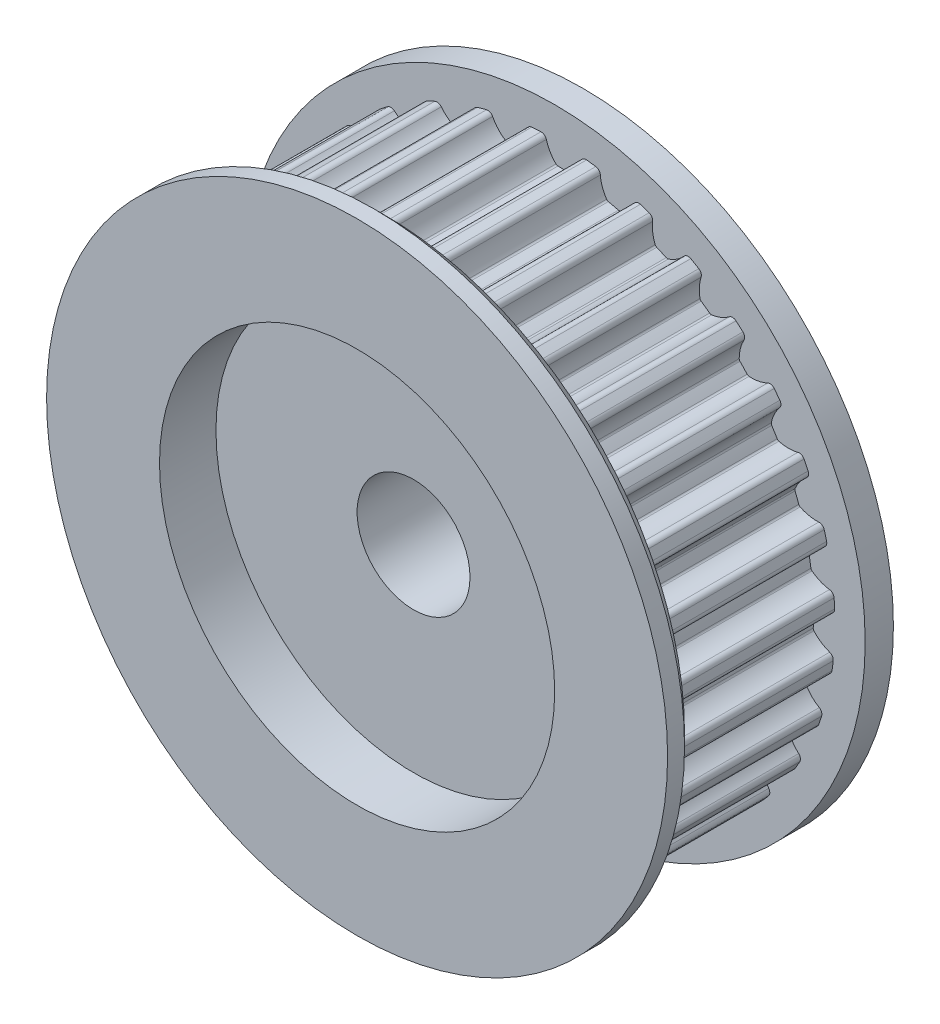
SolidWorks part; units mm, degrees
ref_plane "Front Plane" through (0, 0, 0) normal (0, 0, 1) x (1, 0, 0)
ref_plane "Top Plane" through (0, 0, 0) normal (0, 1, 0) x (1, 0, 0)
ref_plane "Right Plane" through (0, 0, 0) normal (1, 0, 0) x (0, 0, -1)
sketch "Model" plane through (0, 0, 0) normal (0, 0, 1) x (1, 0, 0)
  arc B0 (-2.731, 9.5491) -> (-2.8685, 9.3561) centre (-2.6788, 9.3665) ccw
  arc B1 (-3.0037, 8.6965) -> (-2.8685, 9.3561) centre (-4.1915, 9.2836) ccw
  arc B2 (-3.06, 8.6465) -> (-3.0037, 8.6965) centre (-3.0934, 8.7408) ccw
  arc B3 (-3.06, 8.6465) -> (-3.4049, 8.5166) centre (0, 0) ccw
  arc B4 (-3.4802, 8.517) -> (-3.4049, 8.5166) centre (-3.442, 8.6094) ccw
  arc B5 (-4.017, 8.9235) -> (-3.4802, 8.517) centre (-2.9749, 9.7419) ccw
  arc B6 (-4.017, 8.9235) -> (-4.2477, 8.9779) centre (-4.1664, 8.8061) ccw
  arc B7 (-4.2477, 8.9779) -> (-4.5415, 8.8329) centre (0, 0) ccw
  arc B8 (-4.5415, 8.8329) -> (-4.6387, 8.6167) centre (-4.4546, 8.6639) ccw
  arc B9 (-4.6426, 7.9434) -> (-4.6387, 8.6167) centre (-5.9221, 8.2875) ccw
  arc B10 (-4.688, 7.8834) -> (-4.6426, 7.9434) centre (-4.7392, 7.9693) ccw
  arc B11 (-4.688, 7.8834) -> (-5.001, 7.6887) centre (0, 0) ccw
  arc B12 (-5.0749, 7.6744) -> (-5.001, 7.6887) centre (-5.0555, 7.7725) ccw
  arc B13 (-5.6807, 7.9683) -> (-5.0749, 7.6744) centre (-4.8183, 8.9743) ccw
  arc B14 (-5.6807, 7.9683) -> (-5.9175, 7.9767) centre (-5.8043, 7.8241) ccw
  arc B15 (-5.9175, 7.9767) -> (-6.1774, 7.7771) centre (0, 0) ccw
  arc B16 (-6.1774, 7.7771) -> (-6.2306, 7.5462) centre (-6.0593, 7.6284) ccw
  arc B17 (-6.1031, 6.885) -> (-6.2306, 7.5462) centre (-7.4251, 6.9729) ccw
  arc B18 (-6.1359, 6.8173) -> (-6.1031, 6.885) centre (-6.2028, 6.8916) ccw
  arc B19 (-6.1359, 6.8173) -> (-6.4049, 6.5653) centre (0, 0) ccw
  arc B20 (-6.4746, 6.5369) -> (-6.4049, 6.5653) centre (-6.4747, 6.6369) ccw
  arc B21 (-7.1261, 6.707) -> (-6.4746, 6.5369) centre (-6.4766, 7.8619) ccw
  arc B22 (-7.1261, 6.707) -> (-7.36, 6.669) centre (-7.2192, 6.5414) ccw
  arc B23 (-7.36, 6.669) -> (-7.576, 6.4226) centre (0, 0) ccw
  arc B24 (-7.576, 6.4226) -> (-7.583, 6.1857) centre (-7.431, 6.2997) ccw
  arc B25 (-7.329, 5.5621) -> (-7.583, 6.1857) centre (-8.6428, 5.3904) ccw
  arc B26 (-7.348, 5.4893) -> (-7.329, 5.5621) centre (-7.4281, 5.5491) ccw
  arc B27 (-7.348, 5.4893) -> (-7.5626, 5.1896) centre (0, 0) ccw
  arc B28 (-7.6254, 5.1481) -> (-7.5626, 5.1896) centre (-7.6451, 5.2462) ccw
  arc B29 (-8.2976, 5.1879) -> (-7.6254, 5.1481) centre (-7.8859, 6.4473) ccw
  arc B30 (-8.2976, 5.1879) -> (-8.5196, 5.1049) centre (-8.3567, 5.0073) ccw
  arc B31 (-8.5196, 5.1049) -> (-8.6834, 4.8211) centre (0, 0) ccw
  arc B32 (-8.6834, 4.8211) -> (-8.6441, 4.5874) centre (-8.5173, 4.7289) ccw
  arc B33 (-8.2733, 4.0254) -> (-8.6441, 4.5874) centre (-9.5284, 3.6007) ccw
  arc B34 (-8.2777, 3.9503) -> (-8.2733, 4.0254) centre (-8.368, 3.9933) ccw
  arc B35 (-8.2777, 3.9503) -> (-8.4298, 3.6145) centre (0, 0) ccw
  arc B36 (-8.4833, 3.5616) -> (-8.4298, 3.6145) centre (-8.5217, 3.6539) ccw
  arc B37 (-9.1503, 3.4694) -> (-8.4833, 3.5616) centre (-8.9922, 4.7849) ccw
  arc B38 (-9.1503, 3.4694) -> (-9.3519, 3.3448) centre (-9.173, 3.2808) ccw
  arc B39 (-9.3519, 3.3448) -> (-9.4571, 3.0345) centre (0, 0) ccw
  arc B40 (-9.4571, 3.0345) -> (-9.3729, 2.8129) centre (-9.2762, 2.9764) ccw
  arc B41 (-8.8996, 2.334) -> (-9.3729, 2.8129) centre (-10.0477, 1.6726) ccw
  arc B42 (-8.8893, 2.2594) -> (-8.8996, 2.334) centre (-8.9863, 2.2841) ccw
  arc B43 (-8.8893, 2.2594) -> (-8.9729, 1.9005) centre (0, 0) ccw
  arc B44 (-9.0151, 1.8381) -> (-8.9729, 1.9005) centre (-9.0708, 1.9212) ccw
  arc B45 (-9.6513, 1.6176) -> (-9.0151, 1.8381) centre (-9.7529, 2.9387) ccw
  arc B46 (-9.6513, 1.6176) -> (-9.8247, 1.456) centre (-9.6367, 1.4282) ccw
  arc B47 (-9.8247, 1.456) -> (-9.8674, 1.1312) centre (0, 0) ccw
  arc B48 (-9.8674, 1.1312) -> (-9.7416, 0.9303) centre (-9.6786, 1.1095) ccw
  arc B49 (-9.184, 0.5529) -> (-9.7416, 0.9303) centre (-10.181, -0.3198) ccw
  arc B50 (-9.1593, 0.4818) -> (-9.184, 0.5529) centre (-9.2592, 0.4871) ccw
  arc B51 (-9.1593, 0.4818) -> (-9.1713, 0.1134) centre (0, 0) ccw
  arc B52 (-9.2005, 0.044) -> (-9.1713, 0.1134) centre (-9.2713, 0.1147) ccw
  arc B53 (-9.7814, -0.2963) -> (-9.2005, 0.044) centre (-10.1388, 0.9796) ccw
  arc B54 (-9.7814, -0.2963) -> (-9.92, -0.4886) centre (-9.7302, -0.4793) ccw
  arc B55 (-9.92, -0.4886) -> (-9.8985, -0.8156) centre (0, 0) ccw
  arc B56 (-9.8985, -0.8156) -> (-9.7359, -0.9881) centre (-9.7091, -0.8) ccw
  arc B57 (-9.1154, -1.2494) -> (-9.7359, -0.9881) centre (-9.923, -2.2998) ccw
  arc B58 (-9.0773, -1.3143) -> (-9.1154, -1.2494) centre (-9.1763, -1.3287) ccw
  arc B59 (-9.0773, -1.3143) -> (-9.0172, -1.678) centre (0, 0) ccw
  arc B60 (-9.0323, -1.7517) -> (-9.0172, -1.678) centre (-9.1155, -1.6963) ccw
  arc B61 (-9.5357, -2.1989) -> (-9.0323, -1.7517) centre (-10.1351, -1.0172) ccw
  arc B62 (-9.5357, -2.1989) -> (-9.634, -2.4145) centre (-9.4497, -2.3684) ccw
  arc B63 (-9.634, -2.4145) -> (-9.5491, -2.731) centre (0, 0) ccw
  arc B64 (-9.5491, -2.731) -> (-9.3561, -2.8685) centre (-9.3665, -2.6788) ccw
  arc B65 (-8.6965, -3.0037) -> (-9.3561, -2.8685) centre (-9.2836, -4.1915) ccw
  arc B66 (-8.6465, -3.06) -> (-8.6965, -3.0037) centre (-8.7408, -3.0934) ccw
  arc B67 (-8.6465, -3.06) -> (-8.5166, -3.4049) centre (0, 0) ccw
  arc B68 (-8.517, -3.4802) -> (-8.5166, -3.4049) centre (-8.6094, -3.442) ccw
  arc B69 (-8.9235, -4.017) -> (-8.517, -3.4802) centre (-9.7419, -2.9749) ccw
  arc B70 (-8.9235, -4.017) -> (-8.9779, -4.2477) centre (-8.8061, -4.1664) ccw
  arc B71 (-8.9779, -4.2477) -> (-8.8329, -4.5415) centre (0, 0) ccw
  arc B72 (-8.8329, -4.5415) -> (-8.6167, -4.6387) centre (-8.6639, -4.4546) ccw
  arc B73 (-7.9434, -4.6426) -> (-8.6167, -4.6387) centre (-8.2875, -5.9221) ccw
  arc B74 (-7.8834, -4.688) -> (-7.9434, -4.6426) centre (-7.9693, -4.7392) ccw
  arc B75 (-7.8834, -4.688) -> (-7.6887, -5.001) centre (0, 0) ccw
  arc B76 (-7.6744, -5.0749) -> (-7.6887, -5.001) centre (-7.7725, -5.0555) ccw
  arc B77 (-7.9683, -5.6807) -> (-7.6744, -5.0749) centre (-8.9743, -4.8183) ccw
  arc B78 (-7.9683, -5.6807) -> (-7.9767, -5.9175) centre (-7.8241, -5.8043) ccw
  arc B79 (-7.9767, -5.9175) -> (-7.7771, -6.1774) centre (0, 0) ccw
  arc B80 (-7.7771, -6.1774) -> (-7.5462, -6.2306) centre (-7.6284, -6.0593) ccw
  arc B81 (-6.885, -6.1031) -> (-7.5462, -6.2306) centre (-6.9729, -7.4251) ccw
  arc B82 (-6.8173, -6.1359) -> (-6.885, -6.1031) centre (-6.8916, -6.2028) ccw
  arc B83 (-6.8173, -6.1359) -> (-6.5653, -6.4049) centre (0, 0) ccw
  arc B84 (-6.5369, -6.4746) -> (-6.5653, -6.4049) centre (-6.6369, -6.4747) ccw
  arc B85 (-6.707, -7.1261) -> (-6.5369, -6.4746) centre (-7.8619, -6.4766) ccw
  arc B86 (-6.707, -7.1261) -> (-6.669, -7.36) centre (-6.5414, -7.2192) ccw
  arc B87 (-6.669, -7.36) -> (-6.4226, -7.576) centre (0, 0) ccw
  arc B88 (-6.4226, -7.576) -> (-6.1857, -7.583) centre (-6.2997, -7.431) ccw
  arc B89 (-5.5621, -7.329) -> (-6.1857, -7.583) centre (-5.3904, -8.6428) ccw
  arc B90 (-5.4893, -7.348) -> (-5.5621, -7.329) centre (-5.5491, -7.4281) ccw
  arc B91 (-5.4893, -7.348) -> (-5.1896, -7.5626) centre (0, 0) ccw
  arc B92 (-5.1481, -7.6254) -> (-5.1896, -7.5626) centre (-5.2462, -7.6451) ccw
  arc B93 (-5.1879, -8.2976) -> (-5.1481, -7.6254) centre (-6.4473, -7.8859) ccw
  arc B94 (-5.1879, -8.2976) -> (-5.1049, -8.5196) centre (-5.0073, -8.3567) ccw
  arc B95 (-5.1049, -8.5196) -> (-4.8211, -8.6834) centre (0, 0) ccw
  arc B96 (-4.8211, -8.6834) -> (-4.5874, -8.6441) centre (-4.7289, -8.5173) ccw
  arc B97 (-4.0254, -8.2733) -> (-4.5874, -8.6441) centre (-3.6007, -9.5284) ccw
  arc B98 (-3.9503, -8.2777) -> (-4.0254, -8.2733) centre (-3.9933, -8.368) ccw
  arc B99 (-3.9503, -8.2777) -> (-3.6145, -8.4298) centre (0, 0) ccw
  arc B100 (-3.5616, -8.4833) -> (-3.6145, -8.4298) centre (-3.6539, -8.5217) ccw
  arc B101 (-3.4694, -9.1503) -> (-3.5616, -8.4833) centre (-4.7849, -8.9922) ccw
  arc B102 (-3.4694, -9.1503) -> (-3.3448, -9.3519) centre (-3.2808, -9.173) ccw
  arc B103 (-3.3448, -9.3519) -> (-3.0345, -9.4571) centre (0, 0) ccw
  arc B104 (-3.0345, -9.4571) -> (-2.8129, -9.3729) centre (-2.9764, -9.2762) ccw
  arc B105 (-2.334, -8.8996) -> (-2.8129, -9.3729) centre (-1.6726, -10.0477) ccw
  arc B106 (-2.2594, -8.8893) -> (-2.334, -8.8996) centre (-2.2841, -8.9863) ccw
  arc B107 (-2.2594, -8.8893) -> (-1.9005, -8.9729) centre (0, 0) ccw
  arc B108 (-1.8381, -9.0151) -> (-1.9005, -8.9729) centre (-1.9212, -9.0708) ccw
  arc B109 (-1.6176, -9.6513) -> (-1.8381, -9.0151) centre (-2.9387, -9.7529) ccw
  arc B110 (-1.6176, -9.6513) -> (-1.456, -9.8247) centre (-1.4282, -9.6367) ccw
  arc B111 (-1.456, -9.8247) -> (-1.1312, -9.8674) centre (0, 0) ccw
  arc B112 (-1.1312, -9.8674) -> (-0.9303, -9.7416) centre (-1.1095, -9.6786) ccw
  arc B113 (-0.5529, -9.184) -> (-0.9303, -9.7416) centre (0.3198, -10.181) ccw
  arc B114 (-0.4818, -9.1593) -> (-0.5529, -9.184) centre (-0.4871, -9.2592) ccw
  arc B115 (-0.4818, -9.1593) -> (-0.1134, -9.1713) centre (0, 0) ccw
  arc B116 (-0.044, -9.2005) -> (-0.1134, -9.1713) centre (-0.1147, -9.2713) ccw
  arc B117 (0.2963, -9.7814) -> (-0.044, -9.2005) centre (-0.9796, -10.1388) ccw
  arc B118 (0.2963, -9.7814) -> (0.4886, -9.92) centre (0.4793, -9.7302) ccw
  arc B119 (0.4886, -9.92) -> (0.8156, -9.8985) centre (0, 0) ccw
  arc B120 (0.8156, -9.8985) -> (0.9881, -9.7359) centre (0.8, -9.7091) ccw
  arc B121 (1.2494, -9.1154) -> (0.9881, -9.7359) centre (2.2998, -9.923) ccw
  arc B122 (1.3143, -9.0773) -> (1.2494, -9.1154) centre (1.3287, -9.1763) ccw
  arc B123 (1.3143, -9.0773) -> (1.678, -9.0172) centre (0, 0) ccw
  arc B124 (1.7517, -9.0323) -> (1.678, -9.0172) centre (1.6963, -9.1155) ccw
  arc B125 (2.1989, -9.5357) -> (1.7517, -9.0323) centre (1.0172, -10.1351) ccw
  arc B126 (2.1989, -9.5357) -> (2.4145, -9.634) centre (2.3684, -9.4497) ccw
  arc B127 (2.4145, -9.634) -> (2.731, -9.5491) centre (0, 0) ccw
  arc B128 (2.731, -9.5491) -> (2.8685, -9.3561) centre (2.6788, -9.3665) ccw
  arc B129 (3.0037, -8.6965) -> (2.8685, -9.3561) centre (4.1915, -9.2836) ccw
  arc B130 (3.06, -8.6465) -> (3.0037, -8.6965) centre (3.0934, -8.7408) ccw
  arc B131 (3.06, -8.6465) -> (3.4049, -8.5166) centre (0, 0) ccw
  arc B132 (3.4802, -8.517) -> (3.4049, -8.5166) centre (3.442, -8.6094) ccw
  arc B133 (4.017, -8.9235) -> (3.4802, -8.517) centre (2.9749, -9.7419) ccw
  arc B134 (4.017, -8.9235) -> (4.2477, -8.9779) centre (4.1664, -8.8061) ccw
  arc B135 (4.2477, -8.9779) -> (4.5415, -8.8329) centre (0, 0) ccw
  arc B136 (4.5415, -8.8329) -> (4.6387, -8.6167) centre (4.4546, -8.6639) ccw
  arc B137 (4.6426, -7.9434) -> (4.6387, -8.6167) centre (5.9221, -8.2875) ccw
  arc B138 (4.688, -7.8834) -> (4.6426, -7.9434) centre (4.7392, -7.9693) ccw
  arc B139 (4.688, -7.8834) -> (5.001, -7.6887) centre (0, 0) ccw
  arc B140 (5.0749, -7.6744) -> (5.001, -7.6887) centre (5.0555, -7.7725) ccw
  arc B141 (5.6807, -7.9683) -> (5.0749, -7.6744) centre (4.8183, -8.9743) ccw
  arc B142 (5.6807, -7.9683) -> (5.9175, -7.9767) centre (5.8043, -7.8241) ccw
  arc B143 (5.9175, -7.9767) -> (6.1774, -7.7771) centre (0, 0) ccw
  arc B144 (6.1774, -7.7771) -> (6.2306, -7.5462) centre (6.0593, -7.6284) ccw
  arc B145 (6.1031, -6.885) -> (6.2306, -7.5462) centre (7.4251, -6.9729) ccw
  arc B146 (6.1359, -6.8173) -> (6.1031, -6.885) centre (6.2028, -6.8916) ccw
  arc B147 (6.1359, -6.8173) -> (6.4049, -6.5653) centre (0, 0) ccw
  arc B148 (6.4746, -6.5369) -> (6.4049, -6.5653) centre (6.4747, -6.6369) ccw
  arc B149 (7.1261, -6.707) -> (6.4746, -6.5369) centre (6.4766, -7.8619) ccw
  arc B150 (7.1261, -6.707) -> (7.36, -6.669) centre (7.2192, -6.5414) ccw
  arc B151 (7.36, -6.669) -> (7.576, -6.4226) centre (0, 0) ccw
  arc B152 (7.576, -6.4226) -> (7.583, -6.1857) centre (7.431, -6.2997) ccw
  arc B153 (7.329, -5.5621) -> (7.583, -6.1857) centre (8.6428, -5.3904) ccw
  arc B154 (7.348, -5.4893) -> (7.329, -5.5621) centre (7.4281, -5.5491) ccw
  arc B155 (7.348, -5.4893) -> (7.5626, -5.1896) centre (0, 0) ccw
  arc B156 (7.6254, -5.1481) -> (7.5626, -5.1896) centre (7.6451, -5.2462) ccw
  arc B157 (8.2976, -5.1879) -> (7.6254, -5.1481) centre (7.8859, -6.4473) ccw
  arc B158 (8.2976, -5.1879) -> (8.5196, -5.1049) centre (8.3567, -5.0073) ccw
  arc B159 (8.5196, -5.1049) -> (8.6834, -4.8211) centre (0, 0) ccw
  arc B160 (8.6834, -4.8211) -> (8.6441, -4.5874) centre (8.5173, -4.7289) ccw
  arc B161 (8.2733, -4.0254) -> (8.6441, -4.5874) centre (9.5284, -3.6007) ccw
  arc B162 (8.2777, -3.9503) -> (8.2733, -4.0254) centre (8.368, -3.9933) ccw
  arc B163 (8.2777, -3.9503) -> (8.4298, -3.6145) centre (0, 0) ccw
  arc B164 (8.4833, -3.5616) -> (8.4298, -3.6145) centre (8.5217, -3.6539) ccw
  arc B165 (9.1503, -3.4694) -> (8.4833, -3.5616) centre (8.9922, -4.7849) ccw
  arc B166 (9.1503, -3.4694) -> (9.3519, -3.3448) centre (9.173, -3.2808) ccw
  arc B167 (9.3519, -3.3448) -> (9.4571, -3.0345) centre (0, 0) ccw
  arc B168 (9.4571, -3.0345) -> (9.3729, -2.8129) centre (9.2762, -2.9764) ccw
  arc B169 (8.8996, -2.334) -> (9.3729, -2.8129) centre (10.0477, -1.6726) ccw
  arc B170 (8.8893, -2.2594) -> (8.8996, -2.334) centre (8.9863, -2.2841) ccw
  arc B171 (8.8893, -2.2594) -> (8.9729, -1.9005) centre (0, 0) ccw
  arc B172 (9.0151, -1.8381) -> (8.9729, -1.9005) centre (9.0708, -1.9212) ccw
  arc B173 (9.6513, -1.6176) -> (9.0151, -1.8381) centre (9.7529, -2.9387) ccw
  arc B174 (9.6513, -1.6176) -> (9.8247, -1.456) centre (9.6367, -1.4282) ccw
  arc B175 (9.8247, -1.456) -> (9.8674, -1.1312) centre (0, 0) ccw
  arc B176 (9.8674, -1.1312) -> (9.7416, -0.9303) centre (9.6786, -1.1095) ccw
  arc B177 (9.184, -0.5529) -> (9.7416, -0.9303) centre (10.181, 0.3198) ccw
  arc B178 (9.1593, -0.4818) -> (9.184, -0.5529) centre (9.2592, -0.4871) ccw
  arc B179 (9.1593, -0.4818) -> (9.1713, -0.1134) centre (0, 0) ccw
  arc B180 (9.2005, -0.044) -> (9.1713, -0.1134) centre (9.2713, -0.1147) ccw
  arc B181 (9.7814, 0.2963) -> (9.2005, -0.044) centre (10.1388, -0.9796) ccw
  arc B182 (9.7814, 0.2963) -> (9.92, 0.4886) centre (9.7302, 0.4793) ccw
  arc B183 (9.92, 0.4886) -> (9.8985, 0.8156) centre (0, 0) ccw
  arc B184 (9.8985, 0.8156) -> (9.7359, 0.9881) centre (9.7091, 0.8) ccw
  arc B185 (9.1154, 1.2494) -> (9.7359, 0.9881) centre (9.923, 2.2998) ccw
  arc B186 (9.0773, 1.3143) -> (9.1154, 1.2494) centre (9.1763, 1.3287) ccw
  arc B187 (9.0773, 1.3143) -> (9.0172, 1.678) centre (0, 0) ccw
  arc B188 (9.0323, 1.7517) -> (9.0172, 1.678) centre (9.1155, 1.6963) ccw
  arc B189 (9.5357, 2.1989) -> (9.0323, 1.7517) centre (10.1351, 1.0172) ccw
  arc B190 (9.5357, 2.1989) -> (9.634, 2.4145) centre (9.4497, 2.3684) ccw
  arc B191 (9.634, 2.4145) -> (9.5491, 2.731) centre (0, 0) ccw
  arc B192 (9.5491, 2.731) -> (9.3561, 2.8685) centre (9.3665, 2.6788) ccw
  arc B193 (8.6965, 3.0037) -> (9.3561, 2.8685) centre (9.2836, 4.1915) ccw
  arc B194 (8.6465, 3.06) -> (8.6965, 3.0037) centre (8.7408, 3.0934) ccw
  arc B195 (8.6465, 3.06) -> (8.5166, 3.4049) centre (0, 0) ccw
  arc B196 (8.517, 3.4802) -> (8.5166, 3.4049) centre (8.6094, 3.442) ccw
  arc B197 (8.9235, 4.017) -> (8.517, 3.4802) centre (9.7419, 2.9749) ccw
  arc B198 (8.9235, 4.017) -> (8.9779, 4.2477) centre (8.8061, 4.1664) ccw
  arc B199 (8.9779, 4.2477) -> (8.8329, 4.5415) centre (0, 0) ccw
  arc B200 (8.8329, 4.5415) -> (8.6167, 4.6387) centre (8.6639, 4.4546) ccw
  arc B201 (7.9434, 4.6426) -> (8.6167, 4.6387) centre (8.2875, 5.9221) ccw
  arc B202 (7.8834, 4.688) -> (7.9434, 4.6426) centre (7.9693, 4.7392) ccw
  arc B203 (7.8834, 4.688) -> (7.6887, 5.001) centre (0, 0) ccw
  arc B204 (7.6744, 5.0749) -> (7.6887, 5.001) centre (7.7725, 5.0555) ccw
  arc B205 (7.9683, 5.6807) -> (7.6744, 5.0749) centre (8.9743, 4.8183) ccw
  arc B206 (7.9683, 5.6807) -> (7.9767, 5.9175) centre (7.8241, 5.8043) ccw
  arc B207 (7.9767, 5.9175) -> (7.7771, 6.1774) centre (0, 0) ccw
  arc B208 (7.7771, 6.1774) -> (7.5462, 6.2306) centre (7.6284, 6.0593) ccw
  arc B209 (6.885, 6.1031) -> (7.5462, 6.2306) centre (6.9729, 7.4251) ccw
  arc B210 (6.8173, 6.1359) -> (6.885, 6.1031) centre (6.8916, 6.2028) ccw
  arc B211 (6.8173, 6.1359) -> (6.5653, 6.4049) centre (0, 0) ccw
  arc B212 (6.5369, 6.4746) -> (6.5653, 6.4049) centre (6.6369, 6.4747) ccw
  arc B213 (6.707, 7.1261) -> (6.5369, 6.4746) centre (7.8619, 6.4766) ccw
  arc B214 (6.707, 7.1261) -> (6.669, 7.36) centre (6.5414, 7.2192) ccw
  arc B215 (6.669, 7.36) -> (6.4226, 7.576) centre (0, 0) ccw
  arc B216 (6.4226, 7.576) -> (6.1857, 7.583) centre (6.2997, 7.431) ccw
  arc B217 (5.5621, 7.329) -> (6.1857, 7.583) centre (5.3904, 8.6428) ccw
  arc B218 (5.4893, 7.348) -> (5.5621, 7.329) centre (5.5491, 7.4281) ccw
  arc B219 (5.4893, 7.348) -> (5.1896, 7.5626) centre (0, 0) ccw
  arc B220 (5.1481, 7.6254) -> (5.1896, 7.5626) centre (5.2462, 7.6451) ccw
  arc B221 (5.1879, 8.2976) -> (5.1481, 7.6254) centre (6.4473, 7.8859) ccw
  arc B222 (5.1879, 8.2976) -> (5.1049, 8.5196) centre (5.0073, 8.3567) ccw
  arc B223 (5.1049, 8.5196) -> (4.8211, 8.6834) centre (0, 0) ccw
  arc B224 (4.8211, 8.6834) -> (4.5874, 8.6441) centre (4.7289, 8.5173) ccw
  arc B225 (4.0254, 8.2733) -> (4.5874, 8.6441) centre (3.6007, 9.5284) ccw
  arc B226 (3.9503, 8.2777) -> (4.0254, 8.2733) centre (3.9933, 8.368) ccw
  arc B227 (3.9503, 8.2777) -> (3.6145, 8.4298) centre (0, 0) ccw
  arc B228 (3.5616, 8.4833) -> (3.6145, 8.4298) centre (3.6539, 8.5217) ccw
  arc B229 (3.4694, 9.1503) -> (3.5616, 8.4833) centre (4.7849, 8.9922) ccw
  arc B230 (3.4694, 9.1503) -> (3.3448, 9.3519) centre (3.2808, 9.173) ccw
  arc B231 (3.3448, 9.3519) -> (3.0345, 9.4571) centre (0, 0) ccw
  arc B232 (3.0345, 9.4571) -> (2.8129, 9.3729) centre (2.9764, 9.2762) ccw
  arc B233 (2.334, 8.8996) -> (2.8129, 9.3729) centre (1.6726, 10.0477) ccw
  arc B234 (2.2594, 8.8893) -> (2.334, 8.8996) centre (2.2841, 8.9863) ccw
  arc B235 (2.2594, 8.8893) -> (1.9005, 8.9729) centre (0, 0) ccw
  arc B236 (1.8381, 9.0151) -> (1.9005, 8.9729) centre (1.9212, 9.0708) ccw
  arc B237 (1.6176, 9.6513) -> (1.8381, 9.0151) centre (2.9387, 9.7529) ccw
  arc B238 (1.6176, 9.6513) -> (1.456, 9.8247) centre (1.4282, 9.6367) ccw
  arc B239 (1.456, 9.8247) -> (1.1312, 9.8674) centre (0, 0) ccw
  arc B240 (1.1312, 9.8674) -> (0.9303, 9.7416) centre (1.1095, 9.6786) ccw
  arc B241 (0.5529, 9.184) -> (0.9303, 9.7416) centre (-0.3198, 10.181) ccw
  arc B242 (0.4818, 9.1593) -> (0.5529, 9.184) centre (0.4871, 9.2592) ccw
  arc B243 (0.4818, 9.1593) -> (0.1134, 9.1713) centre (0, 0) ccw
  arc B244 (0.044, 9.2005) -> (0.1134, 9.1713) centre (0.1147, 9.2713) ccw
  arc B245 (-0.2963, 9.7814) -> (0.044, 9.2005) centre (0.9796, 10.1388) ccw
  arc B246 (-0.2963, 9.7814) -> (-0.4886, 9.92) centre (-0.4793, 9.7302) ccw
  arc B247 (-0.4886, 9.92) -> (-0.8156, 9.8985) centre (0, 0) ccw
  arc B248 (-0.8156, 9.8985) -> (-0.9881, 9.7359) centre (-0.8, 9.7091) ccw
  arc B249 (-1.2494, 9.1154) -> (-0.9881, 9.7359) centre (-2.2998, 9.923) ccw
  arc B250 (-1.3143, 9.0773) -> (-1.2494, 9.1154) centre (-1.3287, 9.1763) ccw
  arc B251 (-1.3143, 9.0773) -> (-1.678, 9.0172) centre (0, 0) ccw
  arc B252 (-1.7517, 9.0323) -> (-1.678, 9.0172) centre (-1.6963, 9.1155) ccw
  arc B253 (-2.1989, 9.5357) -> (-1.7517, 9.0323) centre (-1.0172, 10.1351) ccw
  arc B254 (-2.1989, 9.5357) -> (-2.4145, 9.634) centre (-2.3684, 9.4497) ccw
  arc B255 (-2.4145, 9.634) -> (-2.731, 9.5491) centre (0, 0) ccw
sketch_block_instance "Block1-2"
sketch_block "Block1"
extrude "Boss-Extrude1" add sketch "Model" along normal blind 6
sketch "Sketch2" plane through (0, 0, 0) normal (0, 0, -1) x (-1, 0, 0)
  circle A0 centre (0, 0) radius 11
  dimension "D1" = 22
extrude "Boss-Extrude2" add sketch "Sketch2" along normal blind 1
sketch "Sketch3" plane through (0, 0, 6) normal (0, 0, 1) x (1, 0, 0)
  circle A0 centre (0, 0) radius 11
  circle A1 centre (0, 0) radius 11 construction
extrude "Boss-Extrude3" add sketch "Sketch3" along normal blind 1
sketch "Sketch4" plane through (0, 0, 7) normal (0, 0, 1) x (1, 0, 0)
  circle A0 centre (0, 0) radius 2
  dimension "D1" = 4
extrude "Cut-Extrude1" cut sketch "Sketch4" against normal through all
chamfer "Chamfer1" distance 0.4 angle 45 1 edges at (11, 0, 6)
sketch "Sketch5" plane through (0, 0, 7) normal (0, 0, 1) x (1, 0, 0)
  circle A0 centre (0, 0) radius 7
  dimension "D1" = 14
extrude "Cut-Extrude2" cut sketch "Sketch5" against normal blind 2
